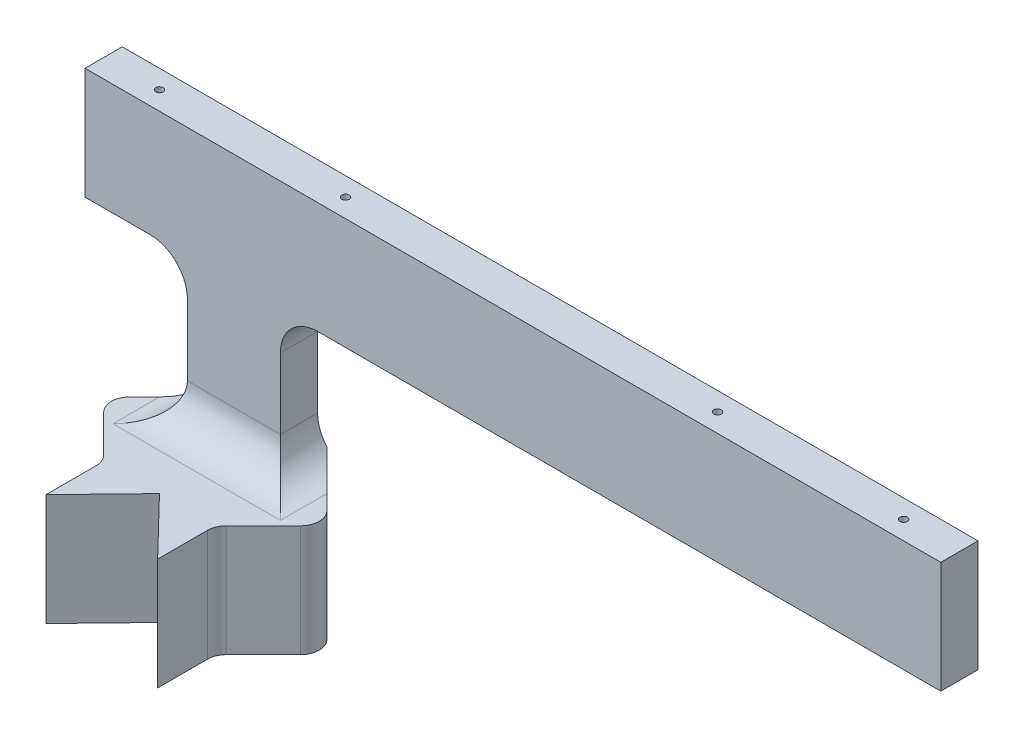
SolidWorks part; units mm, degrees
ref_plane "Front Plane" through (0, 0, 0) normal (0, 0, 1) x (1, 0, 0)
ref_plane "Top Plane" through (0, 0, 0) normal (0, 1, 0) x (1, 0, 0)
ref_plane "Right Plane" through (0, 0, 0) normal (1, 0, 0) x (0, 0, -1)
sketch "Sketch1" plane through (0, 0, 0) normal (0, 0, 1) x (1, 0, 0)
  line L1 (115, 15) -> (-115, 15)
  line L2 (115, 15) -> (115, -15)
  line L3 (115, -15) -> (-115, -15)
  line L4 (-115, 15) -> (-115, -15)
  line L5 (115, 15) -> (-115, -15) construction
  line L6 (115, -15) -> (-115, 15) construction
  point P0 (0, 0)
  dimension "D1" = 230
  dimension "D2" = 30
extrude "Boss-Extrude1" add sketch "Sketch1" along normal blind 10
sketch "Sketch2" plane through (0, 15, 0) normal (0, 1, 0) x (1, 0, 0)
  line L0 (115, -5) -> (-115, -5) construction
  line L1 (115, -10) -> (115, 0) construction
  line L2 (-115, -10) -> (-115, 0) construction
  line L3 (0, -55) -> (0, 55) construction
  circle A0 centre (50, -5) radius 1
  circle A1 centre (100, -5) radius 1
  circle A2 centre (-100, -5) radius 1
  circle A3 centre (-50, -5) radius 1
  point P10 (0, -5)
  dimension "D1" = 2
  dimension "D2" = 2
  dimension "D3" = 50
  dimension "D4" = 50
extrude "Cut-Extrude1" cut sketch "Sketch2" against normal blind 54
sketch "Sketch3" plane through (0, -15, 0) normal (0, -1, 0) x (1, 0, 0)
  line L0 (-115, 10) -> (115, 10) construction
  line L1 (-87.5, 10) -> (-62.5, 10)
  line L2 (-87.5, 10) -> (-87.5, 0)
  line L3 (-87.5, 0) -> (-62.5, 0)
  line L4 (-62.5, 10) -> (-62.5, 0)
  line L5 (-115, 0) -> (115, 0) construction
  point P8 (-75, 0)
  dimension "D1" = 25
  dimension "D2" = 75
extrude "Boss-Extrude2" add sketch "Sketch3" along normal blind 54
fillet "Fillet1" radius 10 2 edges at (-62.5, -15, 5) (-87.5, -15, 5)
sketch "Sketch4" plane through (0, -69, 0) normal (0, -1, 0) x (1, 0, 0)
  line L0 (-62.5, 0) -> (-62.5, 10) construction
  line L1 (-45, 30) -> (-105, 30)
  line L2 (-45, 30) -> (-45, 0)
  line L3 (-45, 0) -> (-105, 0)
  line L4 (-105, 30) -> (-105, 0)
  line L5 (-45, 30) -> (-105, 0) construction
  line L6 (-45, 0) -> (-105, 30) construction
  line L7 (-87.5, 0) -> (-62.5, 0) construction
  point P0 (-75, 15)
  point P5 (0, 0)
  point P8 (-62.5, 5)
  point P11 (-75, 0)
  point P12 (-75, 12.4435)
  dimension "D1" = 30
  dimension "D2" = 60
extrude "Boss-Extrude3" add sketch "Sketch4" against normal mid plane 30
sketch "Sketch6" plane through (0, -84, 0) normal (0, -1, 0) x (1, 0, 0)
  line L0 (-105, 15) -> (-90, 30)
  line L1 (-90, 30) -> (-90, 0)
  line L2 (-90, 0) -> (-105, 15)
  line L3 (-75, 30) -> (-75, 0) construction
  line L4 (-60, 30) -> (-60, 0)
  line L5 (-45, 15) -> (-60, 30)
  line L6 (-60, 0) -> (-45, 15)
  line L7 (-45, 30) -> (-105, 30)
  line L8 (-45, 30) -> (-45, 0)
  line L9 (-45, 0) -> (-105, 0)
  line L10 (-105, 30) -> (-105, 0)
  line L11 (-45, 30) -> (-105, 0) construction
  line L12 (-45, 0) -> (-105, 30) construction
  line L13 (-45, 30) -> (-105, 30) construction
  point P8 (-75, 15)
  point P13 (0, 0)
  point P14 (0, 0)
  point P16 (0, 0)
  point P18 (-90, 30)
  point P21 (-90, 0)
  point P22 (-45, 14.3508)
  line M11 (-105, 30) -> (-105, 0)
  line M12 (-105, 0) -> (-45, 0)
  line M13 (-45, 0) -> (-45, 30)
  line M14 (-45, 30) -> (-105, 30)
  dimension "D1" = 15
  dimension "D2" = 90
extrude "Cut-Extrude3" cut sketch "Sketch6" against normal blind 40 contours L0 M11 M14 | L2 M12 M11 | L5 M13 M14 | L6 M12 M13 | L10 L9 L8 L7
sketch "Sketch7" plane through (0, -84, 0) normal (0, -1, 0) x (1, 0, 0)
  line L0 (-45, 15) -> (-105, 15) construction
  line L1 (-90, 45.5) -> (-75, 30)
  line L2 (-60, 30) -> (-90, 30) construction
  line L3 (-75, 30) -> (-75, 0) construction
  line L4 (-90, 0) -> (-60, 0) construction
  line L5 (-60, 45.5) -> (-90, 45.5)
  line L6 (-60, 45.5) -> (-60, -15.5)
  line L7 (-60, -15.5) -> (-90, -15.5)
  line L8 (-90, 45.5) -> (-90, -15.5)
  line L9 (-60, 45.5) -> (-90, -15.5) construction
  line L10 (-60, -15.5) -> (-90, 45.5) construction
  line L11 (-75, 30) -> (-60, 45.5)
  line L12 (-60, 30) -> (-90, 30)
  line L13 (-90, 30) -> (-90, 45.5)
  point P4 (-75, 15)
  line M10 (-60, 30) -> (-90, 30)
  dimension "D1" = 61
extrude "Boss-Extrude4" add sketch "Sketch7" against normal blind 30 contours L1 L8 M10 | L11 L6 M10
fillet "Fillet2" radius 5 4 edges at (-90, -69, 30) (-105, -69, 15) (-45, -69, 15) (-60, -69, 30)
fillet "Fillet3" radius 10 3 edges at (-62.5, -54, 5) (-87.5, -54, 5) (-75, -54, 10)
